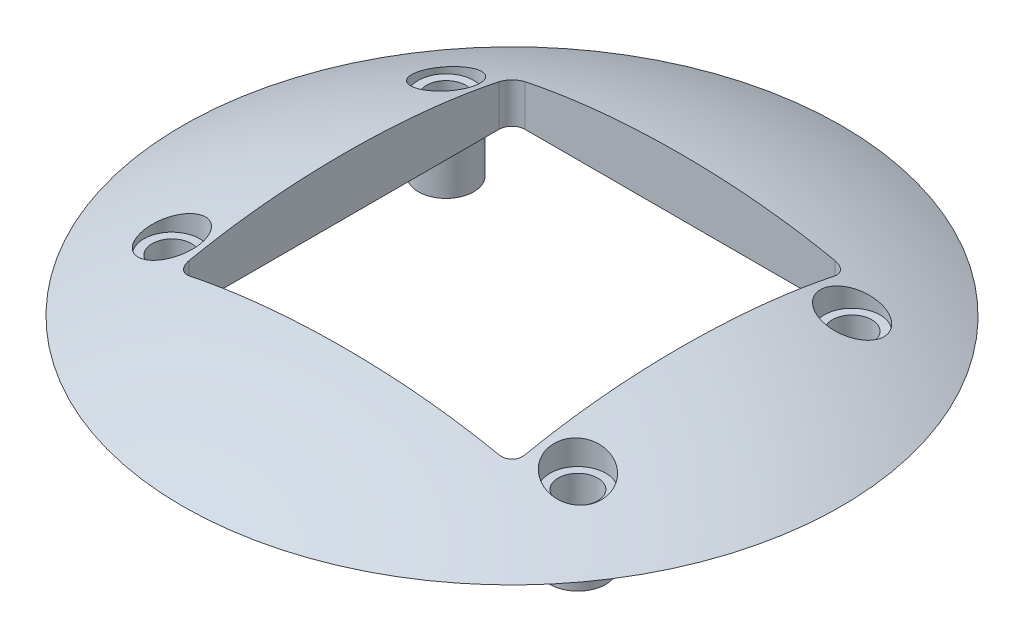
SolidWorks part; units mm, degrees
ref_plane "Front Plane" through (0, 0, 0) normal (0, 0, 1) x (1, 0, 0)
ref_plane "Top Plane" through (0, 0, 0) normal (0, 1, 0) x (1, 0, 0)
ref_plane "Right Plane" through (0, 0, 0) normal (1, 0, 0) x (0, 0, -1)
sketch "Sketch1" plane through (0, 0, 0) normal (0, 0, 1) x (1, 0, 0)
  line L0 (0, 0) -> (-25, 0)
  line L1 (0, 0) -> (0, 5)
  arc A0 (-25, 0) -> (0, 5) centre (-3.832, -40.8401) cw
  dimension "D3" = 46
  dimension "D1" = 25
  dimension "D2" = 5
revolve "Revolve1" add sketch "Sketch1" angle 360 about L1
ref_plane "Plane1" through (0, 0, 0) normal (0, -1, 0) x (-1, 0, 0)
sketch "Sketch2" plane through (0, 0, 0) normal (0, -1, 0) x (-1, 0, 0)
  line L0 (0, 0) -> (0, -6.8501) construction
  line L5 (-15.4, 10.4) -> (15.4, -10.4) construction
  line L6 (-15.4, -10.4) -> (15.4, 10.4) construction
  line L7 (0, 0) -> (6.4069, 0) construction
  circle A0 centre (15.4, -10.4) radius 1.5
  circle A1 centre (-15.4, -10.4) radius 1.5
  circle A2 centre (-15.4, 10.4) radius 1.5
  circle A3 centre (15.4, 10.4) radius 1.5
  point P0 (0, 0)
  dimension "D3" = 3
  dimension "D1" = 30.8
  dimension "D2" = 20.8
extrude "Cut-Extrude1" cut sketch "Sketch2" against normal blind 10
ref_plane "Plane2" through (0, 0, 0) normal (0, -1, 0) x (-1, 0, 0)
sketch "Sketch3" plane through (0, 0, 0) normal (0, -1, 0) x (-1, 0, 0)
  line L1 (11.75, -12.75) -> (-11.75, -12.75)
  line L2 (12.75, -11.75) -> (12.75, 11.75)
  line L3 (11.75, 12.75) -> (-11.75, 12.75)
  line L4 (-12.75, -11.75) -> (-12.75, 11.75)
  line L5 (12.75, -12.75) -> (-12.75, 12.75) construction
  line L6 (12.75, 12.75) -> (-12.75, -12.75) construction
  arc A0 (-12.75, -11.75) -> (-11.75, -12.75) centre (-11.75, -11.75) ccw
  arc A1 (-12.75, 11.75) -> (-11.75, 12.75) centre (-11.75, 11.75) cw
  arc A2 (11.75, 12.75) -> (12.75, 11.75) centre (11.75, 11.75) cw
  arc A3 (12.75, -11.75) -> (11.75, -12.75) centre (11.75, -11.75) cw
  point P0 (0, 0)
  dimension "D3" = 1
  dimension "D1" = 25.5
  dimension "D2" = 25.5
extrude "Cut-Extrude2" cut sketch "Sketch3" against normal blind 7
ref_plane "Plane4" through (0, 5, 0) normal (0, 1, 0) x (1, 0, 0)
sketch "Sketch4" plane through (0, 5, 0) normal (0, 1, 0) x (1, 0, 0)
  line L0 (0, 0) -> (0, 8.1139) construction
  line L1 (0, 0) -> (-7.2315, 0) construction
  circle A0 centre (-15.4, 10.4) radius 2.125
  circle A1 centre (15.4, 10.4) radius 2.125
  circle A2 centre (15.4, -10.4) radius 2.125
  circle A3 centre (-15.4, -10.4) radius 2.125
  dimension "D1" = 4.25
extrude "Cut-Extrude4" cut sketch "Sketch4" against normal blind 3.5
ref_plane "Plane5" through (0, 0, 0) normal (0, -1, 0) x (-1, 0, 0)
sketch "Sketch5" plane through (0, 0, 0) normal (0, -1, 0) x (-1, 0, 0)
  line L0 (0, 0) -> (0, -9.0769) construction
  line L1 (0, 0) -> (6.3759, 0) construction
  circle A0 centre (-15.4, -10.4) radius 2.1
  circle A1 centre (15.4, -10.4) radius 2.1
  circle A2 centre (-15.4, 10.4) radius 2.1
  circle A3 centre (15.4, 10.4) radius 2.1
  circle A4 centre (-15.4, 10.4) radius 1.5
  circle A5 centre (-15.4, -10.4) radius 1.5
  circle A6 centre (15.4, -10.4) radius 1.5
  circle A7 centre (15.4, 10.4) radius 1.5
  dimension "D1" = 4.2
extrude "Boss-Extrude1" add sketch "Sketch5" along normal blind 3.7
